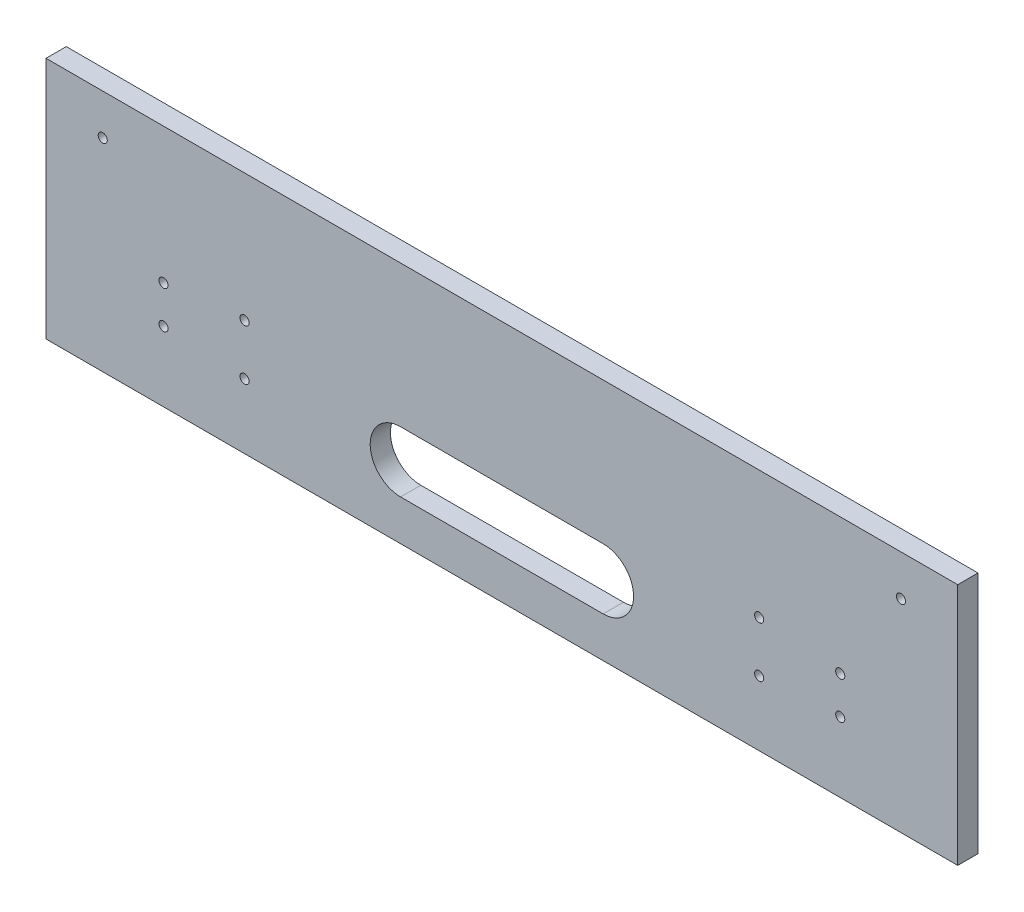
SolidWorks part; units mm, degrees
material "Multistrato di pioppo"
ref_plane "Piano frontale" through (0, 0, 0) normal (0, 0, 1) x (1, 0, 0)
ref_plane "Piano superiore" through (0, 0, 0) normal (0, 1, 0) x (1, 0, 0)
ref_plane "Piano destro" through (0, 0, 0) normal (1, 0, 0) x (0, 0, -1)
sketch "Schizzo1" plane through (0, 0, 0) normal (0, 0, 1) x (1, 0, 0)
  line L1 (-225, 60) -> (225, 60)
  line L2 (-225, 60) -> (-225, -60)
  line L3 (-225, -60) -> (225, -60)
  line L4 (225, 60) -> (225, -60)
  line L5 (-225, 60) -> (225, -60) construction
  line L6 (-225, -60) -> (225, 60) construction
  point P4 (0, 0)
  dimension "D1" = 120
  dimension "D2" = 450
extrude "Estrusione-Estrusione1" add sketch "Schizzo1" along normal blind 10
sketch "Schizzo2" plane through (0, 0, 10) normal (0, 0, 1) x (1, 0, 0)
  line L0 (-50, -25) -> (50, -25) construction
  line L5 (0, -25) -> (0, 0) construction
  line L6 (-225, -60) -> (225, -60) construction
  line L7 (-50, -10) -> (50, -10)
  line L8 (-50, -40) -> (50, -40)
  arc A0 (-50, -10) -> (-50, -40) centre (-50, -25) ccw
  arc A1 (50, -40) -> (50, -10) centre (50, -25) ccw
  point P11 (0, -25)
  dimension "D1" = 130
  dimension "D2" = 30
  dimension "D4" = 20
extrude "Taglio-Estrusione1" cut sketch "Schizzo2" against normal blind 10
sketch "Schizzo3" plane through (0, 0, 0) normal (0, 0, -1) x (-1, 0, 0)
  line L0 (-127, -2) -> (-127, -25) construction
  line L1 (127, -2) -> (127, -25) construction
  line L2 (-225, -60) -> (-225, 60) construction
  line L3 (225, -60) -> (-225, -60) construction
  line L4 (225, 60) -> (225, -60) construction
  circle A0 centre (-167, -7) radius 2.25
  circle A1 centre (-167, -25.5) radius 2.25
  circle A2 centre (167, -7) radius 2.25
  circle A3 centre (167, -25.5) radius 2.25
  circle A5 centre (197, 40) radius 2.25
  circle A7 centre (-197, 40) radius 2.25
  circle A8 centre (-127, -2) radius 2.25 construction
  circle A9 centre (-127, -25) radius 2.25 construction
  circle A10 centre (127, -2) radius 2.25 construction
  circle A11 centre (127, -25) radius 2.25 construction
  point P12 (0, 0)
  point P13 (-197, 40)
  dimension "D1" = 4.5
  dimension "D2" = 23
  dimension "D3" = 98
  dimension "D4" = 58
  dimension "D5" = 98
  dimension "D6" = 58
extrude "Taglio-Estrusione2" cut sketch "Schizzo3" against normal blind 10
sketch "Schizzo4" plane through (0, 0, 10) normal (0, 0, 1) x (1, 0, 0)
  line L0 (-127, -28) -> (-127, -3) construction
  line L1 (-225, 60) -> (-225, -60) construction
  line L2 (-225, -60) -> (225, -60) construction
  line L3 (127, -28) -> (127, -3) construction
  line L4 (225, -60) -> (225, 60) construction
  circle A0 centre (-127, -3) radius 2.25
  circle A1 centre (-127, -28) radius 2.25
  circle A2 centre (127, -28) radius 2.25
  circle A3 centre (127, -3) radius 2.25
  dimension "D1" = 4.5
  dimension "D2" = 98
  dimension "D3" = 32
  dimension "D4" = 25
  dimension "D5" = 25
  dimension "D6" = 32
  dimension "D7" = 98
extrude "Taglio-Estrusione3" cut sketch "Schizzo4" against normal blind 10
